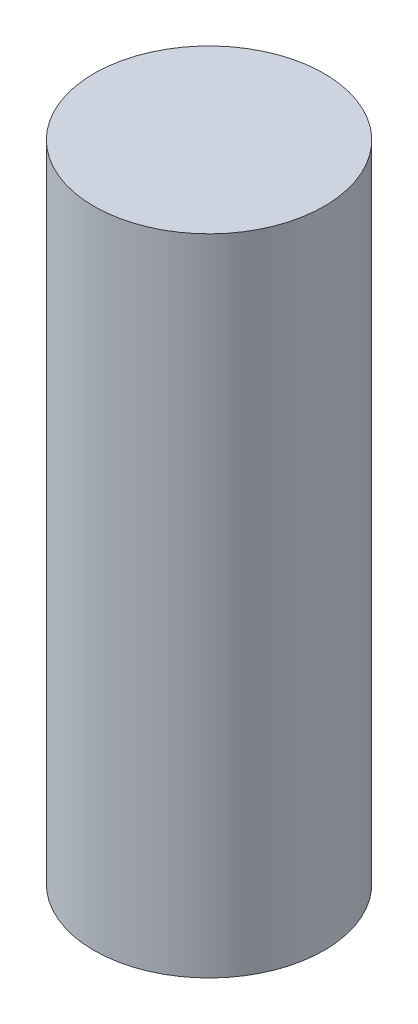
SolidWorks part; units mm, degrees
material "Silicon"
ref_plane "Front Plane" through (0, 0, 0) normal (0, 0, 1) x (1, 0, 0)
ref_plane "Top Plane" through (0, 0, 0) normal (0, 1, 0) x (1, 0, 0)
ref_plane "Right Plane" through (0, 0, 0) normal (1, 0, 0) x (0, 0, -1)
sketch "Sketch1" plane through (0, 0, 0) normal (0, 1, 0) x (1, 0, 0)
  circle A0 centre (0, 0) radius 31.75
  dimension "D1" = 63.5
extrude "Boss-Extrude1" add sketch "Sketch1" along normal blind 177.8
equation "\"Packed Diameter\"= 2.5"
equation "\"Packed Length\"= 7"
equation "\"D1@Sketch1\"=\"Packed Diameter\""
equation "\"D1@Boss-Extrude1\"=\"Packed Length\""
